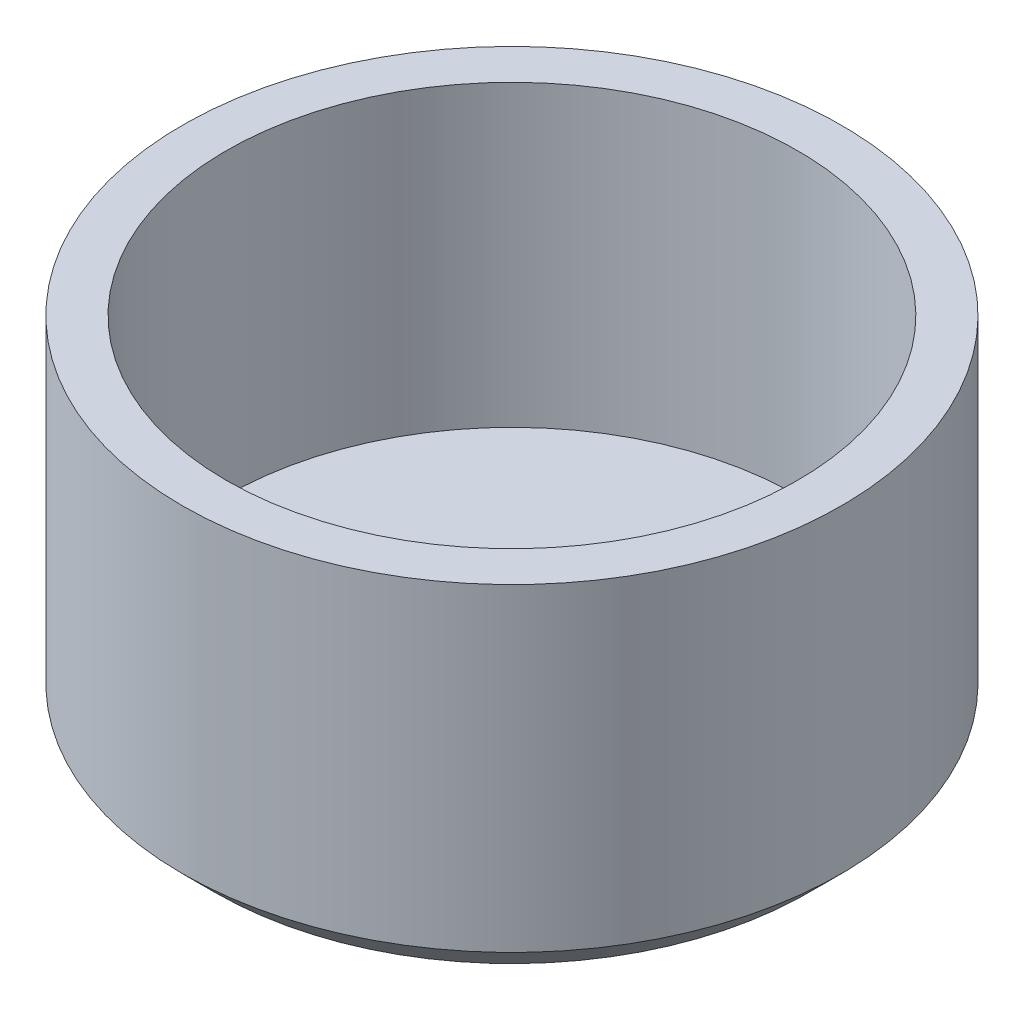
SolidWorks part; units mm, degrees
ref_plane "Front Plane" through (0, 0, 0) normal (0, 0, 1) x (1, 0, 0)
ref_plane "Top Plane" through (0, 0, 0) normal (0, 1, 0) x (1, 0, 0)
ref_plane "Right Plane" through (0, 0, 0) normal (1, 0, 0) x (0, 0, -1)
sketch "Sketch1" plane through (0, 0, 0) normal (0, 1, 0) x (1, 0, 0)
  line L0 (-2.35, 1) -> (3.0983, 1) construction
  line L47 (-1.2689, 0.8) -> (1.2689, 0.8)
  circle A0 centre (0, 0) radius 15
  circle A17 centre (0, 0) radius 10
  circle A38 centre (0, 0) radius 4
  circle A39 centre (0, 0) radius 1.5
  point P7 (0, 0)
  point P26 (0, 0)
  point P44 (0, 0)
  point P92 (0, 0)
  point P98 (0, 0)
  point P116 (0, 0)
  dimension "D1" = 30
  dimension "D2" = 1
  dimension "D3" = 20
  dimension "D10" = 3
  dimension "D11" = 0.8
extrude "Boss-Extrude1" add sketch "Sketch1" along normal blind 16
sketch "Sketch2" plane through (0, 16, 0) normal (0, 1, 0) x (1, 0, 0)
  circle A0 centre (0, 0) radius 13
  dimension "D1" = 26
extrude "Cut-Extrude1" cut sketch "Sketch2" against normal blind 13.6
chamfer "Chamfer1" distance 1.5 angle 45 1 edges at (0, 0, 15)
